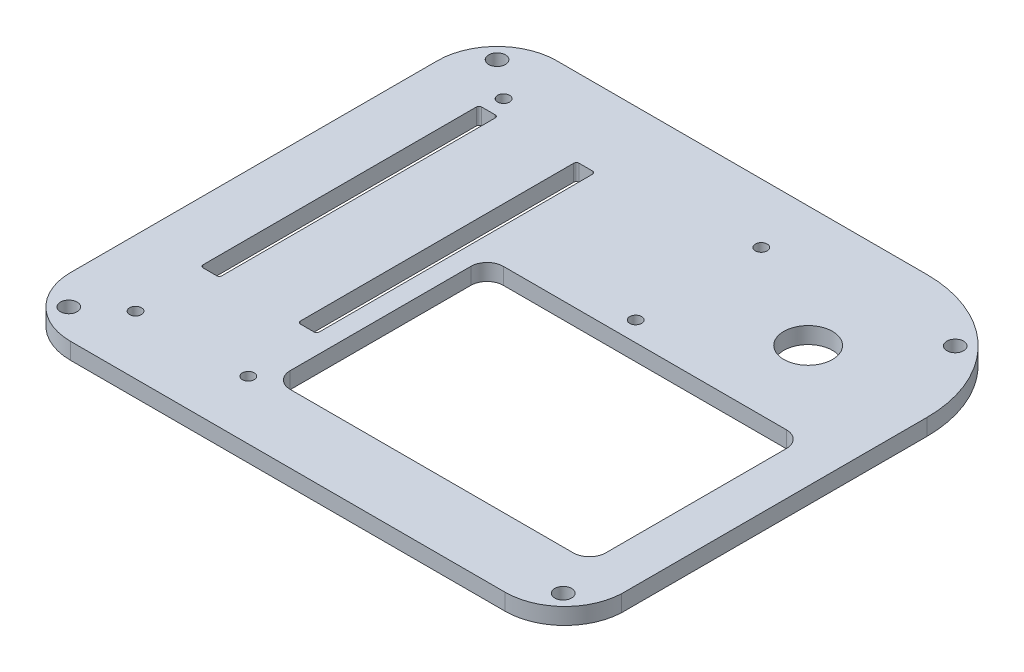
SolidWorks part; units mm, degrees
material "PMMA"
ref_plane "Front Plane" through (0, 0, 0) normal (0, 0, 1) x (1, 0, 0)
ref_plane "Top Plane" through (0, 0, 0) normal (0, 1, 0) x (1, 0, 0)
ref_plane "Right Plane" through (0, 0, 0) normal (1, 0, 0) x (0, 0, -1)
sketch "Sketch2" plane through (0, 0, 0) normal (0, 1, 0) x (1, 0, 0)
  line L0 (28, -66.24) -> (28, -32.84)
  line L1 (3, 0) -> (71.45, 0) construction
  line L2 (0, -3) -> (0, -70.84) construction
  line L3 (3, -73.84) -> (83.3401, -73.84) construction
  line L8 (6.5, -6.84) -> (6.5, -57.34)
  line L9 (3, -6.34) -> (24.5, -6.34) construction
  line L10 (3, -6.84) -> (3, -57.34)
  line L11 (3, -57.84) -> (24.5, -57.84) construction
  line L12 (24.5, -6.84) -> (24.5, -57.34)
  line L17 (21, -6.84) -> (21, -57.34)
  line L18 (3.5, -6.34) -> (6, -6.34)
  line L19 (21.5, -6.34) -> (24, -6.34)
  line L20 (3.5, -57.84) -> (6, -57.84)
  line L21 (21.5, -57.84) -> (24, -57.84)
  line L22 (86.33, -14.88) -> (86.33, -71.0854) construction
  line L23 (31, -29.84) -> (83.33, -29.84)
  line L24 (31, -69.24) -> (83.33, -69.24)
  line L25 (3, 8) -> (71.45, 8)
  line L26 (94.33, -14.88) -> (94.33, -71.3101)
  line L27 (3, -81.84) -> (83.3401, -81.84)
  line L28 (-8, -3) -> (-8, -70.84)
  line L29 (86.33, -32.84) -> (86.33, -66.24)
  line L30 (0.8787, -0.8787) -> (-4.7782, 4.7782) construction
  line L31 (81.9717, -4.3583) -> (87.6286, 1.2986) construction
  line L32 (90.9502, -78.7827) -> (85.3728, -73.0464) construction
  line L33 (-4.7782, -78.6182) -> (0.8787, -72.9613) construction
  arc A0 (86.33, -14.88) -> (71.45, 0) centre (71.45, -14.88) ccw construction
  circle A1 centre (4.19, -71.01) radius 1.1
  circle A2 centre (25.03, -71.01) radius 1.1
  circle A3 centre (4.19, -2.98) radius 1.1
  circle A4 centre (51.82, -2.98) radius 1.1
  circle A5 centre (51.82, -26.2) radius 1.1
  circle A6 centre (82.13, -71.01) radius 1.1 construction
  circle A7 centre (82.13, -26.2) radius 1.1 construction
  circle A8 centre (71.83, -14.33) radius 4.5
  arc A9 (86.33, -71.0854) -> (83.3401, -73.84) centre (83.3401, -70.84) cw construction
  arc A10 (0, -70.84) -> (3, -73.84) centre (3, -70.84) ccw construction
  arc A11 (3, 0) -> (0, -3) centre (3, -3) ccw construction
  arc A13 (28, -66.24) -> (31, -69.24) centre (31, -66.24) ccw
  arc A14 (28, -32.84) -> (31, -29.84) centre (31, -32.84) cw
  arc A16 (6.5, -57.34) -> (6, -57.84) centre (6, -57.34) cw
  arc A17 (3, -57.34) -> (3.5, -57.84) centre (3.5, -57.34) ccw
  arc A18 (21, -57.34) -> (21.5, -57.84) centre (21.5, -57.34) ccw
  arc A19 (24.5, -57.34) -> (24, -57.84) centre (24, -57.34) cw
  arc A20 (24.5, -6.84) -> (24, -6.34) centre (24, -6.84) ccw
  arc A21 (21, -6.84) -> (21.5, -6.34) centre (21.5, -6.84) cw
  arc A22 (6, -6.34) -> (6.5, -6.84) centre (6, -6.84) cw
  arc A23 (3, -6.84) -> (3.5, -6.34) centre (3.5, -6.84) cw
  arc A24 (94.33, -14.88) -> (71.45, 8) centre (71.45, -14.88) ccw
  arc A25 (94.33, -71.3101) -> (83.3401, -81.84) centre (83.3401, -70.84) cw
  arc A26 (-8, -70.84) -> (3, -81.84) centre (3, -70.84) ccw
  arc A27 (3, 8) -> (-8, -3) centre (3, -3) ccw
  arc A28 (86.33, -32.84) -> (83.33, -29.84) centre (83.33, -32.84) ccw
  arc A29 (86.33, -66.24) -> (83.33, -69.24) centre (83.33, -66.24) cw
  circle A30 centre (-2.6569, 2.6569) radius 1.55
  circle A31 centre (85.5073, -0.8227) radius 1.55
  circle A32 centre (88.8589, -76.6318) radius 1.55
  circle A33 centre (-2.6569, -76.4969) radius 1.55
  point P37 (86.33, -73.84)
  point P40 (0, -73.84)
  point P43 (0, 0)
  point P55 (6.5, -57.84)
  point P61 (21, -57.84)
  point P70 (21, -6.34)
  point P73 (6.5, -6.34)
  point P86 (86.33, -29.84)
  point P89 (86.33, -69.24)
  dimension "D1" = 14.88
  dimension "D6" = 2.2
  dimension "D28" = 9
  dimension "D29" = 3
  dimension "D30" = 3
  dimension "D31" = 3
  dimension "D32" = 3
  dimension "D33" = 3
  dimension "D34" = 3
  dimension "D35" = 3
  dimension "D36" = 0.5
  dimension "D37" = 0.5
  dimension "D38" = 0.5
  dimension "D39" = 0.5
  dimension "D40" = 0.5
  dimension "D41" = 0.5
  dimension "D42" = 0.5
  dimension "D43" = 0.5
  dimension "D20" = 3
  dimension "D44" = 3.1
  dimension "D46" = 3.1
  dimension "D48" = 3.1
  dimension "D50" = 3.1
  dimension "D2" = 73.84
  dimension "D3" = 86.33
  dimension "D4" = 2.83
  dimension "D5" = 4.19
  dimension "D7" = 25.03
  dimension "D8" = 2.83
  dimension "D9" = 2.98
  dimension "D10" = 2.98
  dimension "D11" = 47.63
  dimension "D12" = 23.22
  dimension "D13" = 8
  dimension "D14" = 4.6
  dimension "D15" = 2.83
  dimension "D16" = 51.82
  dimension "D17" = 26.2
  dimension "D18" = 28
  dimension "D19" = 44
  dimension "D21" = 16
  dimension "D22" = 21.5
  dimension "D23" = 3
  dimension "D24" = 51.5
  dimension "D25" = 3.5
  dimension "D26" = 3.5
  dimension "D27" = 14.33
  dimension "D45" = 3
  dimension "D47" = 3
  dimension "D49" = 3
extrude "Boss-Extrude1" add sketch "Sketch2" along normal blind 3.048
